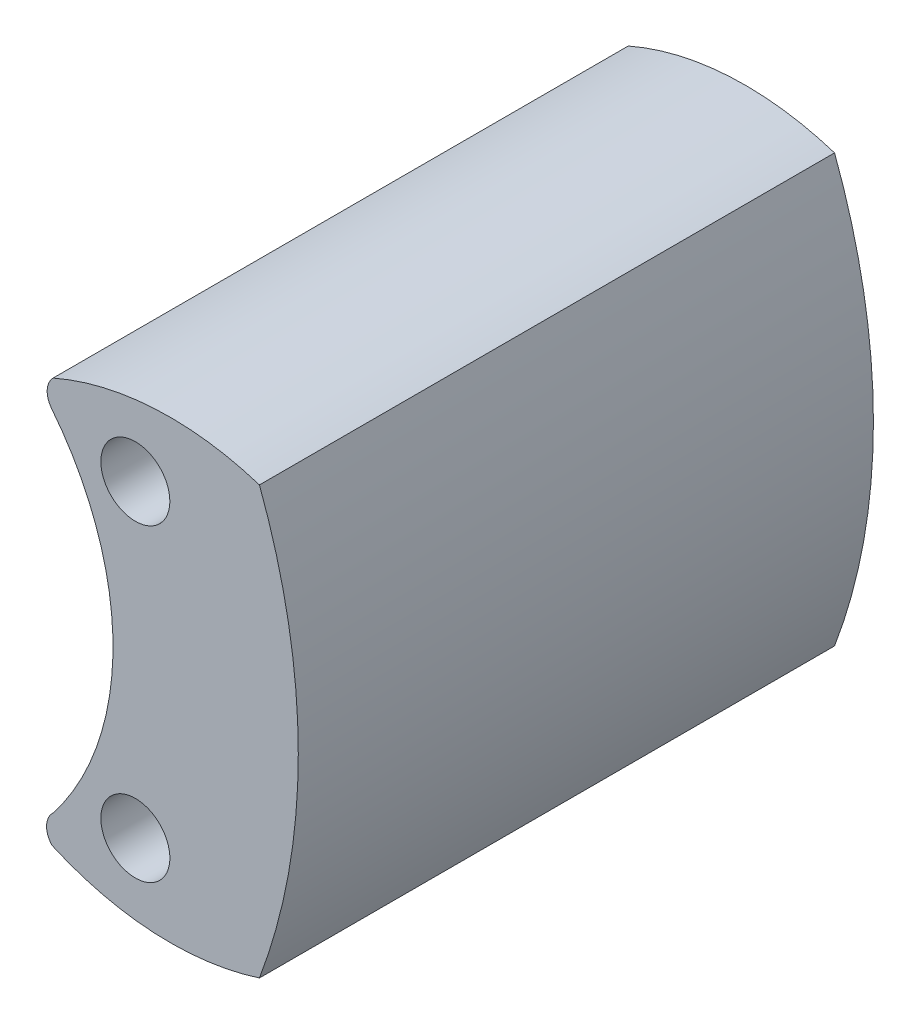
SolidWorks part; units mm, degrees
ref_plane "Front Plane" through (0, 0, 0) normal (0, 0, 1) x (1, 0, 0)
ref_plane "Top Plane" through (0, 0, 0) normal (0, 1, 0) x (1, 0, 0)
ref_plane "Right Plane" through (0, 0, 0) normal (1, 0, 0) x (0, 0, -1)
sketch "Sketch1" plane through (0, 0, 0) normal (0, 0, 1) x (1, 0, 0)
  line L0 (0, 0) -> (0, 9.5) construction
  arc A0 (5.3943, 9.2817) -> (5.3943, -9.2817) centre (-19.2657, 0) cw
  arc A1 (-3.6387, 7.6355) -> (-3.5758, 8.8197) centre (-2.9394, 8.1921) cw
  arc A2 (-3.5758, 8.8197) -> (5.3943, 9.2817) centre (1.5165, -2.7402) cw
  arc A3 (-3.6387, 7.6355) -> (-3.5758, -7.5558) centre (-13.2313, 0) cw
  arc A5 (-3.5758, -7.5558) -> (-3.6256, -8.7977) centre (-2.9797, -8.2016) ccw
  arc A7 (-3.6256, -8.7977) -> (5.3943, -9.2817) centre (1.5165, 2.7402) ccw
extrude "Extrude1" add sketch "Sketch1" along normal blind 25 and the other way blind 0.001
sketch "Sketch3" plane through (0, 0, 25) normal (0, 0, 1) x (1, 0, 0)
  circle A0 centre (0, 6.715) radius 1.5
  circle A1 centre (0, -6.715) radius 1.5
  dimension "D1" = 3
  dimension "D2" = 13.43
extrude "Cut-Extrude1" cut sketch "Sketch3" against normal through all
sketch "Sketch5" plane through (0, 0, -0.001) normal (0, 0, -1) x (-1, 0, 0)
  circle A0 centre (0, 0) radius 4.335
  dimension "D1" = 8.67
extrude "Cut-Extrude2" cut sketch "Sketch5" against normal blind 24
